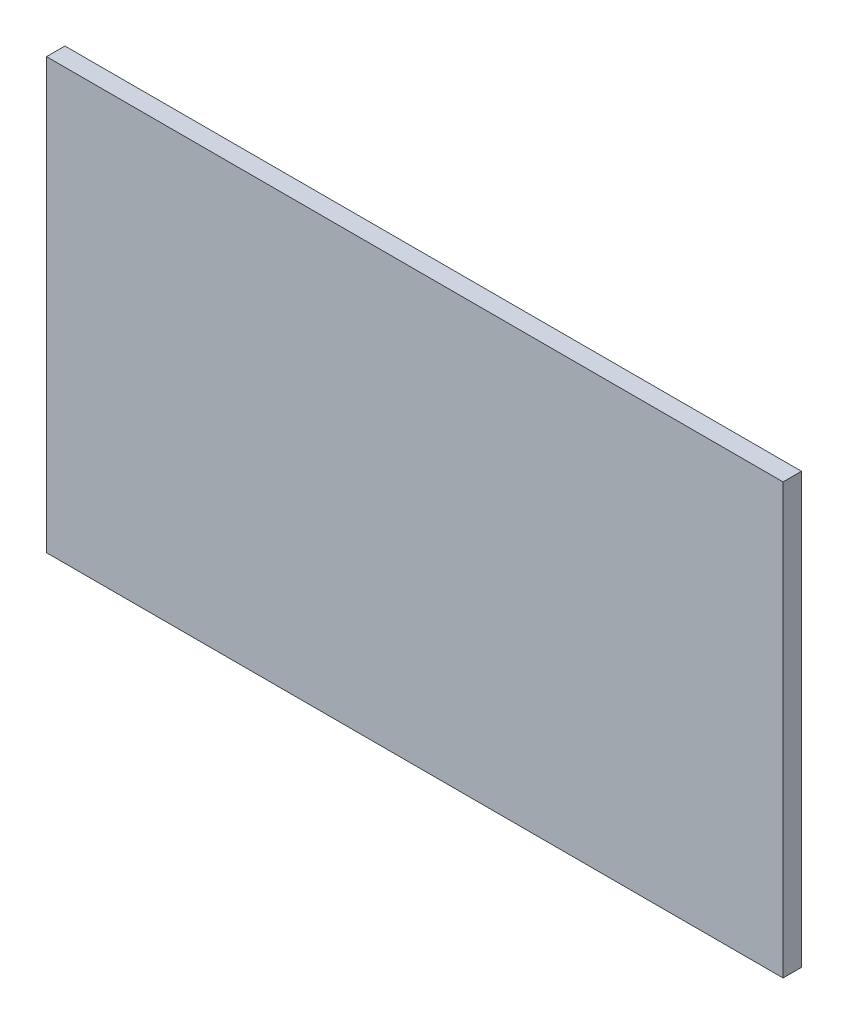
SolidWorks part; units mm, degrees
ref_plane "Front Plane" through (0, 0, 0) normal (0, 0, 1) x (1, 0, 0)
ref_plane "Top Plane" through (0, 0, 0) normal (0, 1, 0) x (1, 0, 0)
ref_plane "Right Plane" through (0, 0, 0) normal (1, 0, 0) x (0, 0, -1)
sketch "Sketch1" plane through (0, 0, 0) normal (0, 0, 1) x (1, 0, 0)
  line L1 (-30, -7.5) -> (30, -7.5)
  line L2 (-30, -7.5) -> (-30, 7.5)
  line L3 (-30, 7.5) -> (30, 7.5)
  line L4 (30, -7.5) -> (30, 7.5)
  line L5 (-30, -7.5) -> (30, 7.5) construction
  line L6 (-30, 7.5) -> (30, -7.5) construction
  point P0 (0, 0)
  dimension "D1" = 60
  dimension "D2" = 15
extrude "Boss-Extrude1" add sketch "Sketch1" along normal blind 3
ref_plane "Plane1" through (0, -2.5, 0) normal (0, -1, 0) x (-1, 0, 0)
sketch "Sketch3" plane through (0, -2.5, 0) normal (0, -1, 0) x (-1, 0, 0)
  line L0 (-14.5, 0) -> (-17.5, 0)
  line L1 (-17.5, 0) -> (-17.5, 3.4)
  line L2 (-17.5, 3.4) -> (-18.9, 3.4)
  line L3 (-18.9, 3.4) -> (-18.9, 5.4)
  line L4 (-18.9, 5.4) -> (-13.1, 5.4)
  line L5 (-13.1, 5.4) -> (-13.1, 3.4)
  line L6 (-13.1, 3.4) -> (-14.5, 3.4)
  line L7 (-14.5, 3.4) -> (-14.5, 0)
  line L8 (0, 0) -> (0, -14.1499) construction
  line L9 (-16, -1.2546) -> (-16, 5.574) construction
  line L10 (16, -1.2546) -> (16, 5.574) construction
  line L11 (14.5, 3.4) -> (14.5, 0)
  line L12 (13.1, 3.4) -> (14.5, 3.4)
  line L13 (13.1, 5.4) -> (13.1, 3.4)
  line L14 (18.9, 5.4) -> (13.1, 5.4)
  line L15 (18.9, 3.4) -> (18.9, 5.4)
  line L16 (17.5, 3.4) -> (18.9, 3.4)
  line L17 (17.5, 0) -> (17.5, 3.4)
  line L18 (14.5, 0) -> (17.5, 0)
  dimension "D1" = 3.4
  dimension "D2" = 5.4
  dimension "D3" = 5.8
  dimension "D4" = 3
  dimension "D5" = 16
extrude "Boss-Extrude2" add sketch "Sketch3" against normal blind 6
sketch "Sketch4" plane through (0, 7.5, 0) normal (0, 1, 0) x (1, 0, 0)
  line L0 (30, 0) -> (22, 0)
  line L1 (30, 0) -> (-30, 0) construction
  line L2 (22, 0) -> (23.5, -1.5)
  line L3 (23.5, -1.5) -> (30, -1.5)
  line L4 (30, -3) -> (30, 0) construction
  line L5 (30, -1.5) -> (30, 0) construction
  line L6 (0, 0) -> (0, -12.1628) construction
  line L7 (0, 0) -> (0, -1.5)
  line L8 (0, -1.5) -> (8.5, -1.5)
  line L9 (8.5, -1.5) -> (10, 0)
  line L10 (10, 0) -> (0, 0)
  line L11 (16, -7.361) -> (16, 10.6801) construction
  line L12 (17.5, 3.4) -> (17.5, 0) construction
  line L13 (14.5, 0) -> (14.5, 3.4) construction
  line L14 (30, -3) -> (-30, -3) construction
  line L15 (30, -1.5) -> (30, 0)
  dimension "D1" = 12
  dimension "D2" = 45
  dimension "D3" = 1.5
  dimension "D4" = 45
extrude "Cut-Extrude1" cut sketch "Sketch4" against normal through all
mirror "Mirror1" about plane through (0, 0, 0) normal (1, 0, 0) of "Cut-Extrude1"
sketch "Sketch5" plane through (0, 7.5, 0) normal (0, 1, 0) x (1, 0, 0)
  line L0 (30, -3) -> (-30, -3)
  line L1 (-30, -3) -> (-30, -1.5)
  line L2 (-30, -3) -> (-30, -1.5) construction
  line L3 (-30, -1.5) -> (30, -1.5)
  line L4 (30, -3) -> (30, -1.5) construction
  line L5 (30, -1.5) -> (30, -3)
  dimension "D1" = 1.5
extrude "Boss-Extrude3" add sketch "Sketch5" along normal blind 10
mirror "Mirror2" about plane through (0, 0, 0) normal (0, 1, 0) of "Boss-Extrude3"
